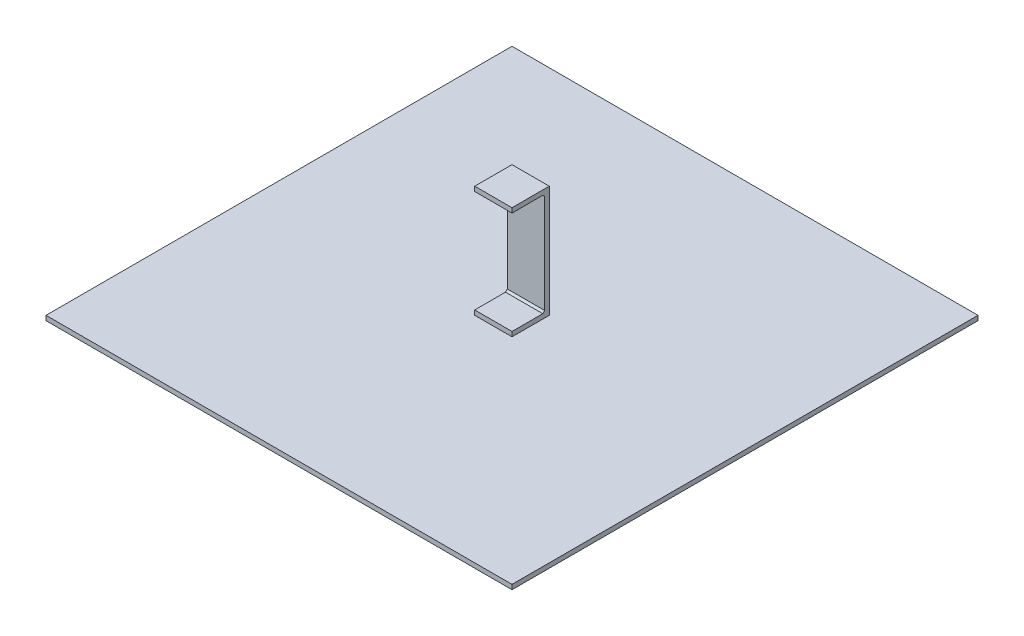
SolidWorks part; units mm, degrees
ref_plane "Front Plane" through (0, 0, 0) normal (0, 0, 1) x (1, 0, 0)
ref_plane "Top Plane" through (0, 0, 0) normal (0, 1, 0) x (1, 0, 0)
ref_plane "Right Plane" through (0, 0, 0) normal (1, 0, 0) x (0, 0, -1)
sketch "Sketch1" plane through (0, 0, 0) normal (1, 0, 0) x (0, 0, -1)
  line L0 (-104.9852, 50) -> (295.0148, 50)
  line L1 (295.0148, 50) -> (295.0148, -1150)
  line L2 (295.0148, -1150) -> (-104.9852, -1150)
  line L3 (-104.9852, -1150) -> (-104.9852, -1100)
  line L4 (-104.9852, -1100) -> (245.0148, -1100)
  line L5 (245.0148, -1100) -> (245.0148, 0)
  line L6 (245.0148, 0) -> (-104.9852, 0)
  line L7 (-104.9852, 0) -> (-104.9852, 50)
  dimension "D1" = 400
  dimension "D2" = 1200
  dimension "D3" = 400
  dimension "D4" = 50
  dimension "D5" = 50
  dimension "D6" = 50
extrude "Boss-Extrude1" add sketch "Sketch1" along normal blind 400
chamfer "Chamfer1" distance 20 angle 45 2 edges at (200, -1100, -245.0148) (200, 0, -245.0148)
sketch "Sketch2" plane through (0, -1150, 0) normal (0, -1, 0) x (1, 0, 0)
  line L0 (0, -95.0148) -> (400, -95.0148) construction
  line L2 (-2300, 2404.9852) -> (2700, 2404.9852)
  line L3 (-2300, 2404.9852) -> (-2300, -2595.0148)
  line L4 (0, 104.9852) -> (0, -295.0148)
  line L5 (0, -295.0148) -> (400, -295.0148)
  line L6 (400, -295.0148) -> (400, 104.9852)
  line L7 (400, 104.9852) -> (0, 104.9852)
  line L8 (0, 104.9852) -> (0, -295.0148)
  line L9 (0, -295.0148) -> (400, -295.0148)
  line L10 (400, -295.0148) -> (400, 104.9852)
  line L11 (400, 104.9852) -> (0, 104.9852)
  line L12 (-2300, -2595.0148) -> (2700, -2595.0148)
  line L13 (2700, 2404.9852) -> (2700, -2595.0148)
  line L14 (-2300, 2404.9852) -> (2700, -2595.0148) construction
  line L15 (-2300, -2595.0148) -> (2700, 2404.9852) construction
  point P6 (200, -95.0148)
  dimension "D2" = 5000
  dimension "D3" = 5000
  dimension "D1" = 0
extrude "Boss-Extrude2" add sketch "Sketch2" along normal blind 50 separate body
